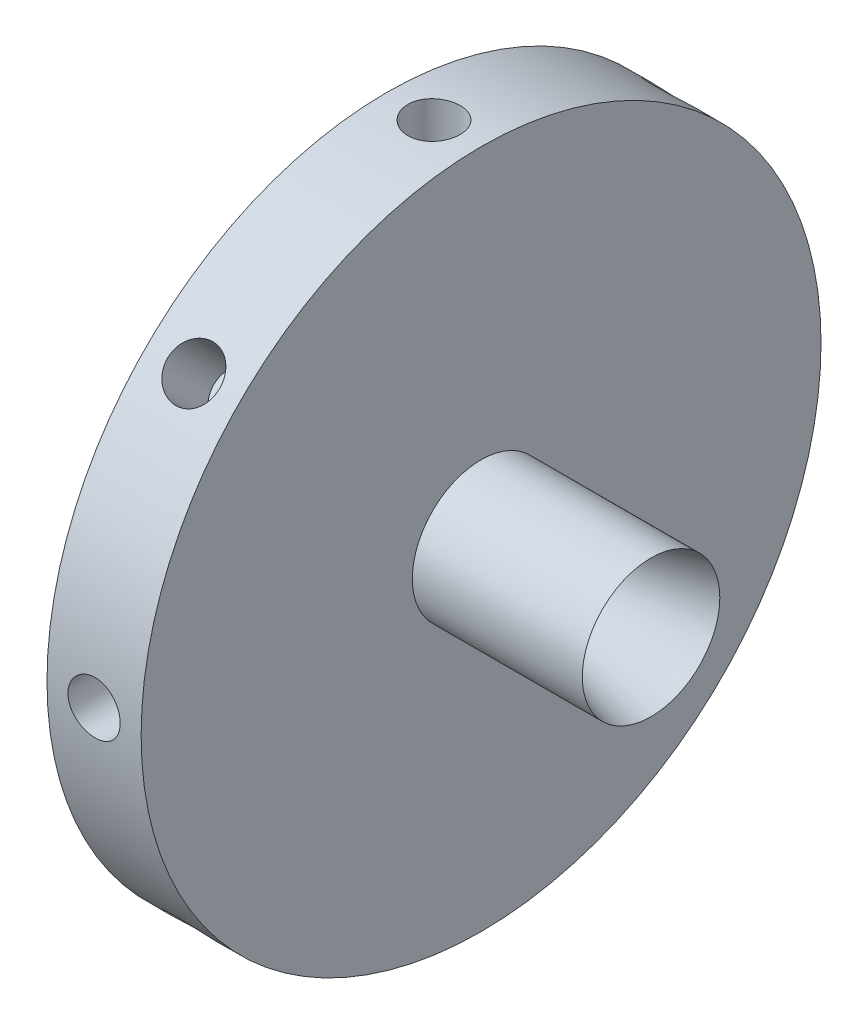
SolidWorks part; units mm, degrees
ref_plane "Front Plane" through (0, 0, 0) normal (0, 0, 1) x (1, 0, 0)
ref_plane "Top Plane" through (0, 0, 0) normal (0, 1, 0) x (1, 0, 0)
ref_plane "Right Plane" through (0, 0, 0) normal (1, 0, 0) x (0, 0, -1)
sketch "Sketch1" plane through (0, 0, 0) normal (0, 0, 1) x (1, 0, 0)
  line L0 (20.2, 0) -> (0, 0) construction
  line L3 (0, 26) -> (7.2, 26)
  line L5 (7.2, 5.26) -> (20.2, 5.26)
  line L9 (0, 0) -> (-33.839, 0) construction
  line L10 (0, 26) -> (0, 0)
  line L11 (-14.8425, 0) -> (61.8565, 0) construction
  line L12 (0, 0) -> (20.2, 0)
  line L13 (6.2, 2) -> (0, 18)
  line L14 (7.2, 26) -> (7.2, 5.26)
  line L15 (20.2, 5.26) -> (20.2, 0)
  line L17 (7.2, 2) -> (6.2, 2)
  line L18 (7.2, 2) -> (20.2, 5.26)
  line L20 (0, 26) -> (0, 0)
  line L21 (0, 0) -> (20.2, 0)
  line L22 (20.2, 0) -> (20.2, 5.26)
  line L23 (20.2, 5.26) -> (7.2, 2)
  line L24 (7.2, 2) -> (6.2, 2)
  point P3 (0, 22.5983)
  point P6 (0, 19.8033)
  point P7 (0, 0)
  dimension "D1" = 7.2
  dimension "D2" = 13
  dimension "D3" = 26
  dimension "D4" = 5.26
  dimension "D5" = 1
  dimension "D6" = 2
  dimension "D7" = 18
  dimension "D8" = 6.2
revolve "Revolve2" add sketch "Sketch1" angle 360 about L0
ref_plane "Plane1" through (0, 0, -26) normal (0, 0, -1) x (-1, 0, 0)
sketch "Sketch2" plane through (0, 0, -26) normal (0, 0, -1) x (-1, 0, 0)
  line L0 (0, -26) -> (0, 26) construction
  circle A0 centre (-3.6, 0) radius 2
  dimension "D1" = 4
  dimension "D2" = 3.6
extrude "Cut-Extrude1" cut sketch "Sketch2" against normal blind 5
pattern_circular "CirPattern1" count 8 over 360 about axis through (0, 0, 0) along (1, 0, 0) of "Cut-Extrude1"
